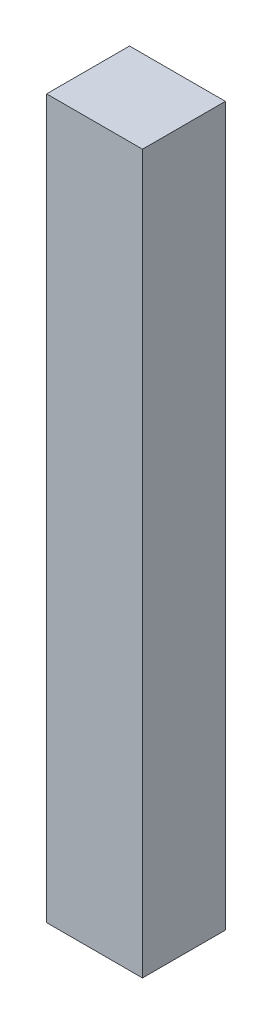
SolidWorks part; units mm, degrees
ref_plane "Front Plane" through (0, 0, 0) normal (0, 0, 1) x (1, 0, 0)
ref_plane "Top Plane" through (0, 0, 0) normal (0, 1, 0) x (1, 0, 0)
ref_plane "Right Plane" through (0, 0, 0) normal (1, 0, 0) x (0, 0, -1)
sketch "Sketch1" plane through (0, 0, 0) normal (0, 0, 1) x (1, 0, 0)
  line L1 (-16.8547, -43.6115) -> (-7.1632, -43.6115)
  line L2 (-16.8547, -43.6115) -> (-16.8547, 28.967)
  line L3 (-16.8547, 28.967) -> (-7.1632, 28.967)
  line L4 (-7.1632, -43.6115) -> (-7.1632, 28.967)
extrude "Boss-Extrude1" add sketch "Sketch1" along normal blind 8.382 contours L2 L3 L4 L1
